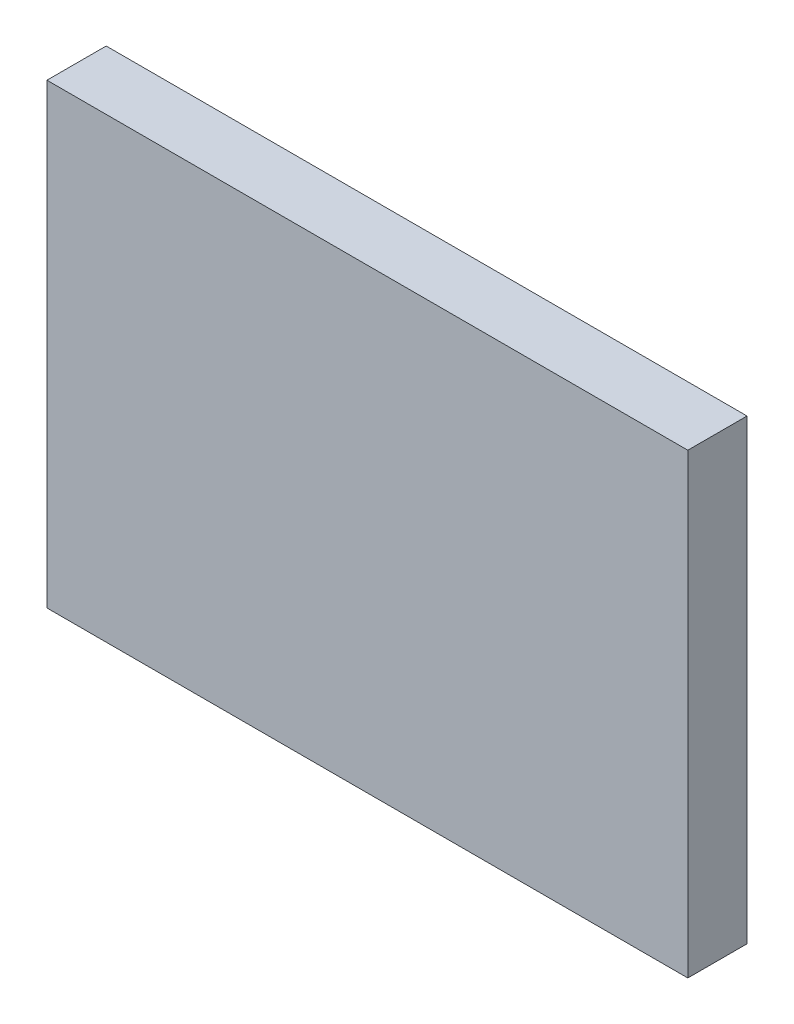
SolidWorks part; units mm, degrees
ref_plane "Front Plane" through (0, 0, 0) normal (0, 0, 1) x (1, 0, 0)
ref_plane "Top Plane" through (0, 0, 0) normal (0, 1, 0) x (1, 0, 0)
ref_plane "Right Plane" through (0, 0, 0) normal (1, 0, 0) x (0, 0, -1)
sketch "Sketch1" plane through (0, 0, 0) normal (0, 0, 1) x (1, 0, 0)
  line B0 (-68.7, 55.35) -> (-68.7, 0)
  line B1 (0, 0) -> (0, 55.35)
  line B2 (-68.7, 0) -> (0, 0)
  line B3 (0, 55.35) -> (-68.7, 55.35)
  line B4 (-68.7, 0) -> (0, 0)
sketch_block_instance "Back_OC-1"
sketch_block "Back_OC"
extrude "Boss-Extrude1" add sketch "Sketch1" along normal blind 6.35 contours B1 B3 B0 B2
sketch "Sketch2" plane through (0, 0, 0) normal (0, -1, 0) x (1, 0, 0)
  line L4 (-68.7, 0) -> (0, 0)
  line L5 (0, 0) -> (0, 6.35)
  line L6 (0, 6.35) -> (-68.7, 6.35)
  line L7 (-68.7, 6.35) -> (-68.7, 0)
  line L8 (-68.7, 0) -> (0, 0)
  line L9 (0, 0) -> (0, 6.35)
  line L10 (0, 6.35) -> (-68.7, 6.35)
  line L11 (-68.7, 6.35) -> (-68.7, 0)
  dimension "D1" = 0
extrude "Cut-Extrude1" cut sketch "Sketch2" against normal blind 6.35
